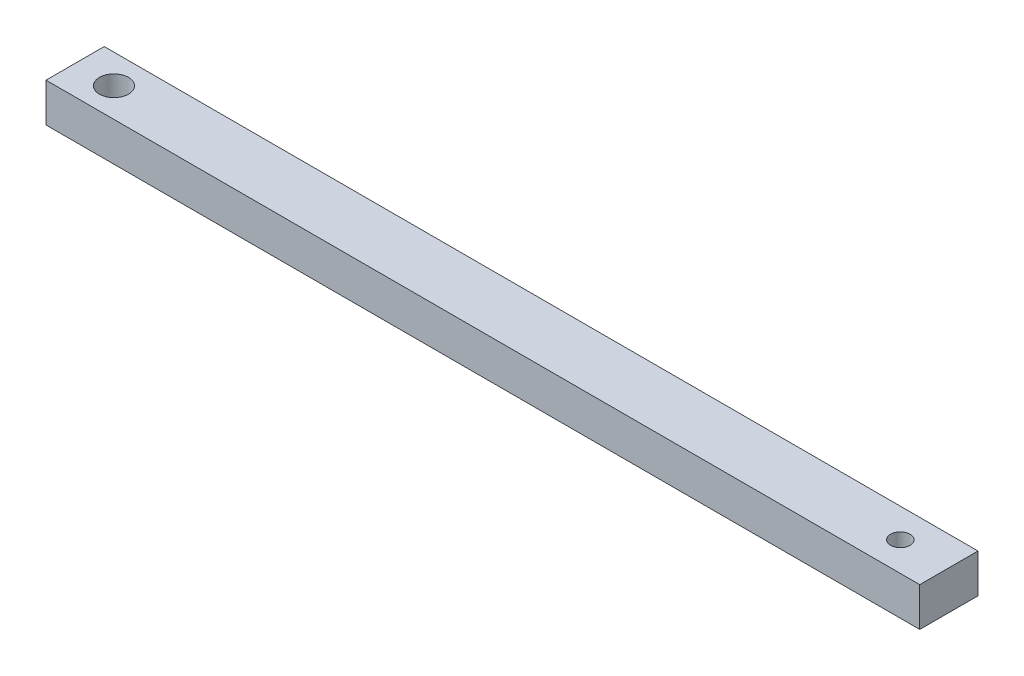
SolidWorks part; units mm, degrees
ref_plane "前视基准面" through (0, 0, 0) normal (0, 0, 1) x (1, 0, 0)
ref_plane "上视基准面" through (0, 0, 0) normal (0, 1, 0) x (1, 0, 0)
ref_plane "右视基准面" through (0, 0, 0) normal (1, 0, 0) x (0, 0, -1)
sketch "草图1" plane through (0, 0, 0) normal (0, 0, 1) x (1, 0, 0)
  line L1 (-225, 10) -> (225, 10)
  line L2 (-225, 10) -> (-225, -10)
  line L3 (-225, -10) -> (225, -10)
  line L4 (225, 10) -> (225, -10)
  line L5 (-225, 10) -> (225, -10) construction
  line L6 (-225, -10) -> (225, 10) construction
  point P0 (0, 0)
  dimension "D1" = 450
  dimension "D2" = 20
extrude "凸台-拉伸1" add sketch "草图1" along normal blind 30
sketch "草图2" plane through (0, 10, 0) normal (0, 1, 0) x (1, 0, 0)
  line L0 (-225, -15) -> (-342.9783, -15) construction
  line L1 (-225, -30) -> (-225, 0) construction
  line L2 (-205, -30) -> (-205, 0) construction
  line L3 (225, -30) -> (-225, -30) construction
  line L4 (225, 0) -> (-225, 0) construction
  circle A0 centre (-205, -15) radius 7.5
  dimension "D2" = 15
  dimension "D1" = 20
extrude "切除-拉伸1" cut sketch "草图2" against normal blind 30 contours A0
sketch "草图3" plane through (0, 10, 0) normal (0, 1, 0) x (1, 0, 0)
  line L0 (225, -15) -> (335.3736, -15) construction
  line L1 (225, -30) -> (225, 0) construction
  line L2 (200, -30) -> (200, 0) construction
  line L3 (225, -30) -> (-225, -30) construction
  line L4 (225, 0) -> (-225, 0) construction
  circle A0 centre (200, -15) radius 5
  dimension "D2" = 10
  dimension "D1" = 25
extrude "切除-拉伸2" cut sketch "草图3" against normal through all
